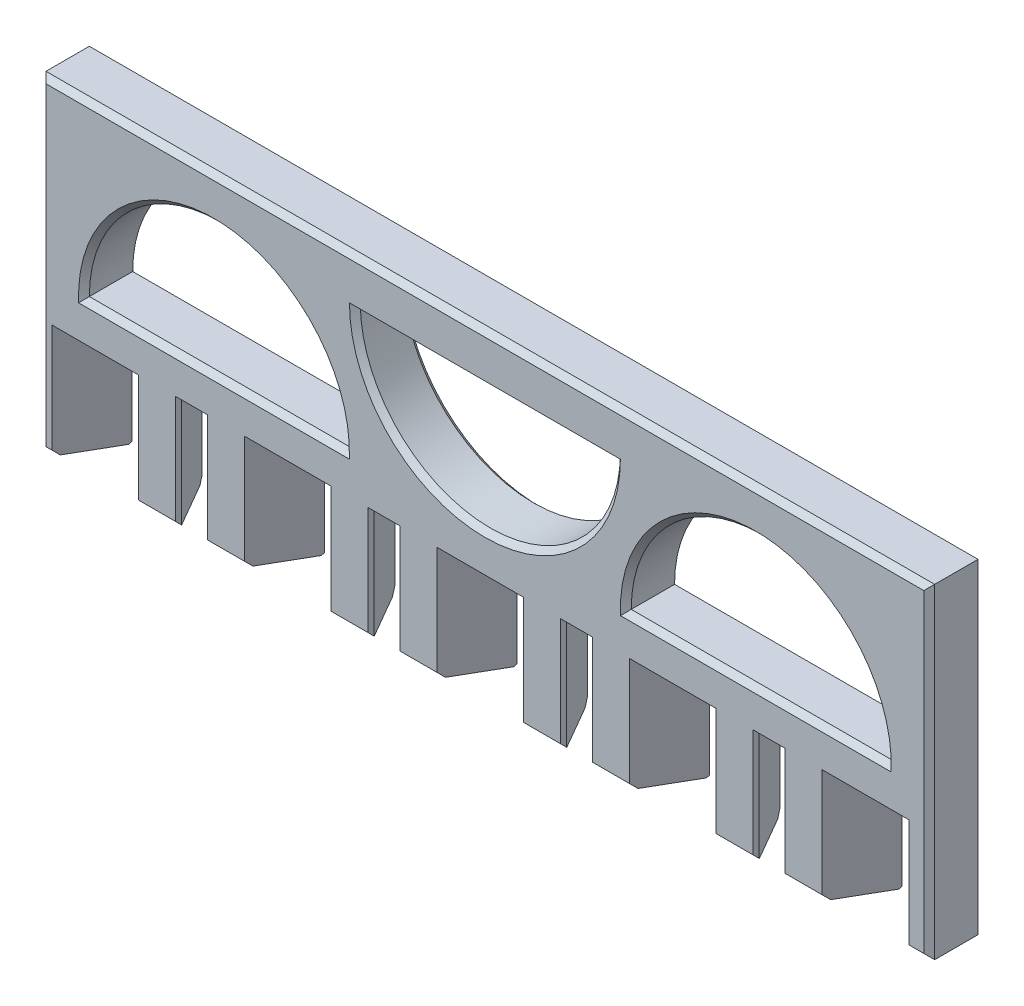
SolidWorks part; units mm, degrees
material "PET"
ref_plane "Front Plane" through (0, 0, 0) normal (0, 0, 1) x (1, 0, 0)
ref_plane "Top Plane" through (0, 0, 0) normal (0, 1, 0) x (1, 0, 0)
ref_plane "Right Plane" through (0, 0, 0) normal (1, 0, 0) x (0, 0, -1)
sketch "Sketch1" plane through (0, 0, 0) normal (0, 0, 1) x (1, 0, 0)
  line L1 (0, 0) -> (82, 0)
  line L2 (0, 0) -> (0, 30)
  line L3 (0, 30) -> (82, 30)
  line L4 (82, 0) -> (82, 30)
  dimension "D1" = 82
  dimension "D2" = 30
extrude "Boss-Extrude1" add sketch "Sketch1" along normal blind 5
sketch "Sketch2" plane through (0, 0, 0) normal (0, -1, 0) x (1, 0, 0)
  line L0 (1.1465, 5) -> (4.0332, 0) construction
  line L1 (4.0332, 0) -> (6.0332, 0) construction
  line L2 (6.0332, 0) -> (8.92, 5) construction
  line L3 (0, 5) -> (82, 5) construction
  line L4 (10.0332, 0) -> (12.92, 5) construction
  line L5 (0, 0) -> (82, 0) construction
  line L6 (12.92, 5) -> (14.92, 5) construction
  line L7 (14.92, 5) -> (17.8068, 0) construction
  line L8 (0, 5) -> (0, 0) construction
  line L9 (1.1465, 5) -> (8.92, 5) construction
  line L10 (10.0332, 0) -> (17.8068, 0) construction
  line L11 (18.9165, 5) -> (26.69, 5) construction
  line L12 (23.8032, 0) -> (26.69, 5) construction
  line L13 (21.8032, 0) -> (23.8032, 0) construction
  line L14 (18.9165, 5) -> (21.8032, 0) construction
  line L15 (27.8032, 0) -> (35.5768, 0) construction
  line L16 (32.69, 5) -> (35.5768, 0) construction
  line L17 (30.69, 5) -> (32.69, 5) construction
  line L18 (27.8032, 0) -> (30.69, 5) construction
  line L19 (36.6865, 5) -> (44.46, 5) construction
  line L20 (41.5732, 0) -> (44.46, 5) construction
  line L21 (39.5732, 0) -> (41.5732, 0) construction
  line L22 (36.6865, 5) -> (39.5732, 0) construction
  line L23 (45.5732, 0) -> (53.3468, 0) construction
  line L24 (50.46, 5) -> (53.3468, 0) construction
  line L25 (48.46, 5) -> (50.46, 5) construction
  line L26 (45.5732, 0) -> (48.46, 5) construction
  line L27 (54.4565, 5) -> (62.23, 5) construction
  line L28 (59.3432, 0) -> (62.23, 5) construction
  line L29 (57.3432, 0) -> (59.3432, 0) construction
  line L30 (54.4565, 5) -> (57.3432, 0) construction
  line L31 (63.3432, 0) -> (71.1168, 0) construction
  line L32 (68.23, 5) -> (71.1168, 0) construction
  line L33 (66.23, 5) -> (68.23, 5) construction
  line L34 (63.3432, 0) -> (66.23, 5) construction
  line L35 (72.2265, 5) -> (80, 5) construction
  line L36 (77.1132, 0) -> (80, 5) construction
  line L37 (75.1132, 0) -> (77.1132, 0) construction
  line L38 (72.2265, 5) -> (75.1132, 0) construction
  line L43 (81.1132, 0) -> (84, 5) [skipped]
  line L44 (84, 5) -> (86, 5) [skipped]
  line L45 (86, 5) -> (88.8868, 0) [skipped]
  line L46 (81.1132, 0) -> (88.8868, 0) [skipped]
  line L47 (0.9733, 5.1) -> (9.0932, 5.1)
  line L48 (6.091, -0.1) -> (9.0932, 5.1)
  line L49 (3.9755, -0.1) -> (6.091, -0.1)
  line L50 (0.9733, 5.1) -> (3.9755, -0.1)
  line L51 (9.86, -0.1) -> (17.98, -0.1)
  line L52 (14.9777, 5.1) -> (17.98, -0.1)
  line L53 (12.8623, 5.1) -> (14.9777, 5.1)
  line L54 (9.86, -0.1) -> (12.8623, 5.1)
  line L55 (18.7433, 5.1) -> (26.8632, 5.1)
  line L56 (23.861, -0.1) -> (26.8632, 5.1)
  line L57 (21.7455, -0.1) -> (23.861, -0.1)
  line L58 (18.7433, 5.1) -> (21.7455, -0.1)
  line L59 (27.63, -0.1) -> (35.75, -0.1)
  line L60 (32.7477, 5.1) -> (35.75, -0.1)
  line L61 (30.6323, 5.1) -> (32.7477, 5.1)
  line L62 (27.63, -0.1) -> (30.6323, 5.1)
  line L63 (36.5133, 5.1) -> (44.6332, 5.1)
  line L64 (41.631, -0.1) -> (44.6332, 5.1)
  line L65 (39.5155, -0.1) -> (41.631, -0.1)
  line L66 (36.5133, 5.1) -> (39.5155, -0.1)
  line L67 (45.4, -0.1) -> (53.52, -0.1)
  line L68 (50.5177, 5.1) -> (53.52, -0.1)
  line L69 (48.4023, 5.1) -> (50.5177, 5.1)
  line L70 (45.4, -0.1) -> (48.4023, 5.1)
  line L71 (54.2833, 5.1) -> (62.4032, 5.1)
  line L72 (59.401, -0.1) -> (62.4032, 5.1)
  line L73 (57.2855, -0.1) -> (59.401, -0.1)
  line L74 (54.2833, 5.1) -> (57.2855, -0.1)
  line L75 (63.17, -0.1) -> (71.29, -0.1)
  line L76 (68.2877, 5.1) -> (71.29, -0.1)
  line L77 (66.1723, 5.1) -> (68.2877, 5.1)
  line L78 (63.17, -0.1) -> (66.1723, 5.1)
  line L79 (72.0533, 5.1) -> (80.1732, 5.1)
  line L80 (77.171, -0.1) -> (80.1732, 5.1)
  line L81 (75.0555, -0.1) -> (77.171, -0.1)
  line L82 (72.0533, 5.1) -> (75.0555, -0.1)
  line L84 (82, 5) -> (82, 0) construction
  dimension "D1" = 30
  dimension "D2" = 60
  dimension "D3" = 60
  dimension "D4" = 60
  dimension "D5" = 2
  dimension "D6" = 2
  dimension "D7" = 4
  dimension "D8" = 2
  dimension "D9" = 5
  dimension "D10" = 3.9965
  dimension "D11" = 0.1
extrude "Cut-Extrude1" cut sketch "Sketch2" against normal blind 10
chamfer "Chamfer1" distance 0.5 angle 45 56 edges at (79.6144, 0, 0) (81.0577, 0, 5) (76.1132, 10, 0) (76.1132, 10, 5) (73.115, 0, 0) (70.2282, 0, 5) (67.23, 10, 0) (67.23, 10, 5) (61.3432, 0, 0) (64.23, 0, 5) (58.3432, 10, 0) (58.3432, 10, 5) (55.345, 0, 0) (52.4582, 0, 5) (49.46, 10, 0) (49.46, 10, 5) (43.5732, 0, 0) (46.46, 0, 5) (40.5732, 10, 0) (40.5732, 10, 5) (37.575, 0, 0) (34.6882, 0, 5) (31.69, 10, 5) (31.69, 10, 0) (25.8032, 0, 0) (28.69, 0, 5) (22.8032, 10, 0) (13.92, 10, 0) (13.92, 10, 5) (22.8032, 10, 5) (16.9182, 0, 5) (19.805, 0, 0) (8.0332, 0, 0) (10.92, 0, 5) (5.0332, 10, 5) (5.0332, 10, 0) (1.9589, 0, 0) (0.5155, 0, 5) (12.8045, 5, 5) (15.0355, 5, 5) (30.5745, 5, 5) (32.8055, 5, 5) (48.3445, 5, 5) (50.5755, 5, 5) (66.1145, 5, 5) (68.3455, 5, 5) (77.2287, 5, 0) (74.9978, 5, 0) (59.4587, 5, 0) (57.2278, 5, 0) (41.6887, 5, 0) (39.4578, 5, 0) (23.9187, 5, 0) (21.6878, 5, 0) (6.1487, 5, 0) (3.9178, 5, 0)
sketch "Sketch11" plane through (0, 0, 5) normal (0, 0, 1) x (1, 0, 0)
  line L3 (4, 14) -> (78, 14) construction
  line L4 (62.0568, 10) -> (54.6297, 10) construction
  line L5 (4, 14) -> (28, 14)
  line L6 (78, 0.5) -> (78, 26)
  line L7 (4, 26) -> (4, 0.5)
  line L8 (78, 26) -> (4, 26)
  line L9 (78, 14) -> (78, 26) construction
  line L10 (4, 26) -> (4, 14) construction
  line L11 (78, 26) -> (4, 26) construction
  line L12 (29, 26) -> (53, 26)
  line L13 (54, 14) -> (78, 14)
  arc A0 (29, 26) -> (53, 26) centre (41, 26) ccw
  arc A1 (28, 14) -> (4, 14) centre (16, 14) ccw
  arc A2 (78, 14) -> (54, 14) centre (66, 14) ccw
  dimension "D2" = 4
  dimension "D1" = 4
extrude "Cut-Extrude3" cut sketch "Sketch11" against normal up to next
chamfer "Chamfer3" distance 0.5 angle 45 17 edges at (82, 15.25, 0) (0, 15.25, 0) (41, 30, 0) (0, 15.25, 5) (41, 30, 5) (41, 14, 5) (66, 14, 0) (66, 26, 0) (66, 14, 5) (66, 26, 5) (41, 14, 0) (41, 26, 0) (16, 14, 0) (16, 26, 0) (16, 14, 5) (16, 26, 5) (82, 15.25, 5)
